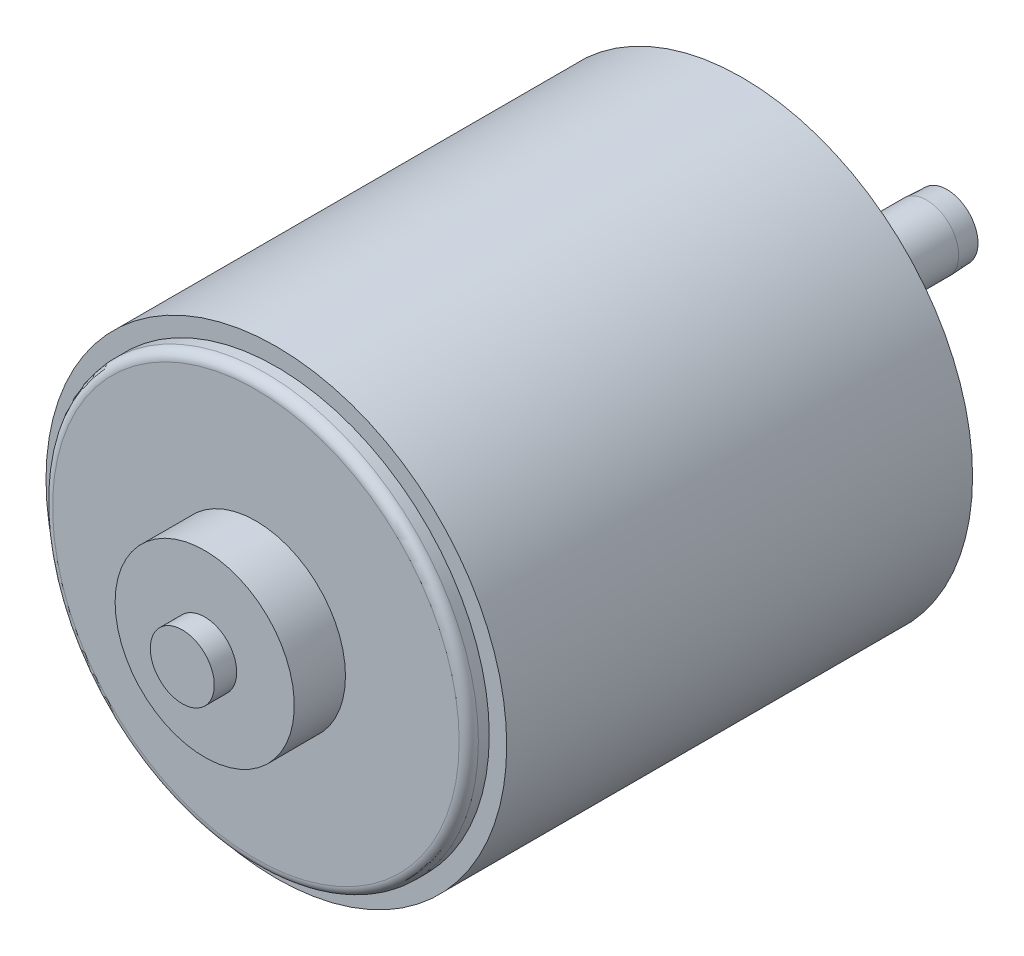
SolidWorks part; units mm, degrees
ref_plane "Front Plane" through (0, 0, 0) normal (0, 0, 1) x (1, 0, 0)
ref_plane "Top Plane" through (0, 0, 0) normal (0, 1, 0) x (1, 0, 0)
ref_plane "Right Plane" through (0, 0, 0) normal (1, 0, 0) x (0, 0, -1)
sketch "Sketch1" plane through (0, 0, 0) normal (0, 0, 1) x (1, 0, 0)
  circle A0 centre (0, 0) radius 18
  dimension "D1" = 36
extrude "Boss-Extrude1" add sketch "Sketch1" along normal blind 38
sketch "Sketch2" plane through (0, 0, 0) normal (0, 0, -1) x (-1, 0, 0)
  circle A0 centre (0, 0) radius 2.5
  dimension "D1" = 5
extrude "Boss-Extrude2" add sketch "Sketch2" along normal blind 16 and the other way blind 45
sketch "Sketch3" plane through (0, 0, 0) normal (0, 0, -1) x (-1, 0, 0)
  circle A0 centre (0, 0) radius 7
  dimension "D1" = 14
extrude "Boss-Extrude3" add sketch "Sketch3" along normal blind 4
hole_wizard "M3x0.5 Tapped Hole1" positions "Sketch4" profile "Sketch5" tap size "M3x0.5" standard "ANSI Metric"
sketch "Sketch4" plane through (0, 0, 0) normal (0, 0, -1) x (-1, 0, 0)
  circle A0 centre (0, 0) radius 12.5
  point P0 (0, 12.5)
  point P8 (-10.8253, 6.25)
  point P10 (0, -12.5)
  point P12 (10.8253, 6.25)
  dimension "D1" = 25
  dimension "D2" = 120
  dimension "D3" = 60
sketch "Sketch5" plane through (0, 12.5, 0) normal (1, 0, 0) x (0, 1, 0)
  line L0 (0, 0) -> (0, 3.7511)
  line L1 (0, 3.7511) -> (1.25, 3)
  line L2 (1.25, 3) -> (1.25, 0)
  line L5 (1.25, 0) -> (0, 0)
  line L10 (0, 3.7511) -> (-1.25, 3) construction
  line L11 (0, -6.35) -> (0, 107.95) construction
  dimension "Tap Drill Dia." = 2.5
  dimension "Tap Drill Depth" = 3
  dimension "Drill Angle" = 118
cosmetic thread "Hole Thread1" parameters "D1"=3, "D2"=3
cosmetic thread "Hole Thread2" parameters "D1"=3, "D2"=3
cosmetic thread "Hole Thread3" parameters "D1"=3, "D2"=3
cosmetic thread "Hole Thread4" parameters "D1"=3, "D2"=3
sketch "Sketch6" plane through (0, 0, 45) normal (0, 0, 1) x (1, 0, 0)
  circle A1 centre (0, 0) radius 2.5
  circle A2 centre (0, 0) radius 2.5
  dimension "D1" = 0
extrude "Cut-Extrude1" cut sketch "Sketch6" against normal offset from surface (1.25 mm away) 59.75 up to face at (-2.5, 0, -16)
ref_plane "Plane1" through (0, 0, 19) normal (0, 0, -1) x (-1, 0, 0)
mirror "Mirror1" about plane through (0, 0, 19) normal (0, 0, -1) of "Boss-Extrude3"
sketch "Sketch7" plane through (0, 0, 38) normal (0, 0, 1) x (1, 0, 0)
  circle A0 centre (0, 0) radius 16.635
  circle A1 centre (0, 0) radius 18
  circle A2 centre (0, 0) radius 18
  dimension "D2" = 33.27
  dimension "D1" = 0
extrude "Cut-Extrude2" cut sketch "Sketch7" against normal blind 1.6
fillet "Fillet1" radius 0.75 1 edges at (16.635, 0, 38)
sketch "Sketch8" plane through (0, 0, 0) normal (0, 1, 0) x (1, 0, 0)
  line L0 (0, 16) -> (0, 50016) construction
  line L1 (2.5, 16) -> (-2.5, 16) construction
  line L2 (2.5, 16) -> (2.5, 14.4125)
  line L3 (2.5, 4) -> (2.5, 16) construction
  line L4 (2.5, 14.4125) -> (2.4238, 16)
  line L5 (2.4238, 16) -> (2.5, 16)
  point P4 (0, 16)
  dimension "D1" = 1.5875
  dimension "D2" = 0.0762
revolve "Cut-Revolve1" cut sketch "Sketch8" angle 360 about L0
